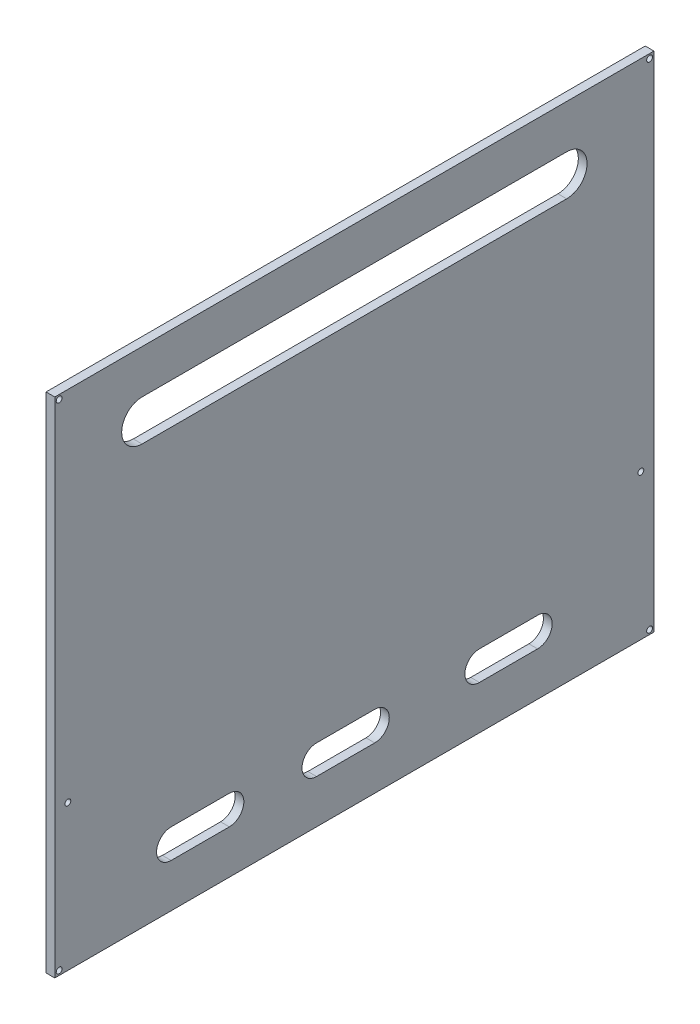
SolidWorks part; units mm, degrees
ref_plane "Front Plane" through (0, 0, 0) normal (0, 0, 1) x (1, 0, 0)
ref_plane "Top Plane" through (0, 0, 0) normal (0, 1, 0) x (1, 0, 0)
ref_plane "Right Plane" through (0, 0, 0) normal (1, 0, 0) x (0, 0, -1)
sketch "Sketch1" plane through (0, 0, 0) normal (1, 0, 0) x (0, 0, -1)
  line L0 (30, 151) -> (176, 151) construction
  line L1 (0, 0) -> (206, 0)
  line L2 (0, 0) -> (0, 173)
  line L3 (0, 173) -> (206, 173)
  line L4 (206, 0) -> (206, 173)
  line L5 (30, 158) -> (176, 158)
  line L6 (30, 144) -> (176, 144)
  line L7 (40, 20) -> (60, 20) construction
  line L8 (40, 25) -> (60, 25)
  line L9 (40, 15) -> (60, 15)
  line L10 (90, 20) -> (110, 20) construction
  line L11 (90, 25) -> (110, 25)
  line L12 (90, 15) -> (110, 15)
  line L13 (146, 20) -> (166, 20) construction
  line L14 (146, 25) -> (166, 25)
  line L15 (146, 15) -> (166, 15)
  arc A0 (30, 158) -> (30, 144) centre (30, 151) ccw
  arc A1 (176, 144) -> (176, 158) centre (176, 151) ccw
  arc A2 (40, 25) -> (40, 15) centre (40, 20) ccw
  arc A3 (60, 15) -> (60, 25) centre (60, 20) ccw
  arc A4 (90, 25) -> (90, 15) centre (90, 20) ccw
  arc A5 (110, 15) -> (110, 25) centre (110, 20) ccw
  arc A6 (146, 25) -> (146, 15) centre (146, 20) ccw
  arc A7 (166, 15) -> (166, 25) centre (166, 20) ccw
  circle A8 centre (204.5, 171.5) radius 1
  circle A9 centre (204.5, 1.5) radius 1
  circle A10 centre (1.5, 171.5) radius 1
  circle A11 centre (1.5, 1.5) radius 1
  circle A12 centre (201.5, 50) radius 1
  circle A13 centre (4.5, 50) radius 1
  point P7 (103, 151)
  point P14 (50, 20)
  point P20 (100, 20)
  point P27 (156, 20)
  dimension "D3" = 7
  dimension "D5" = 30
  dimension "D17" = 2
  dimension "D18" = 2
  dimension "D19" = 2
  dimension "D20" = 2
  dimension "D29" = 2
  dimension "D31" = 2
  dimension "D1" = 173
  dimension "D2" = 206
  dimension "D4" = 15
  dimension "D6" = 30
  dimension "D7" = 20
  dimension "D8" = 20
  dimension "D9" = 20
  dimension "D10" = 40
  dimension "D11" = 40
  dimension "D12" = 60
  dimension "D13" = 20
  dimension "D14" = 15
  dimension "D15" = 15
  dimension "D16" = 15
  dimension "D21" = 1.5
  dimension "D22" = 1.5
  dimension "D23" = 1.5
  dimension "D24" = 1.5
  dimension "D25" = 1.5
  dimension "D26" = 1.5
  dimension "D27" = 1.5
  dimension "D28" = 1.5
  dimension "D30" = 4.5
  dimension "D32" = 4.5
  dimension "D33" = 50
  dimension "D34" = 50
extrude "Boss-Extrude1" add sketch "Sketch1" along normal blind 3
